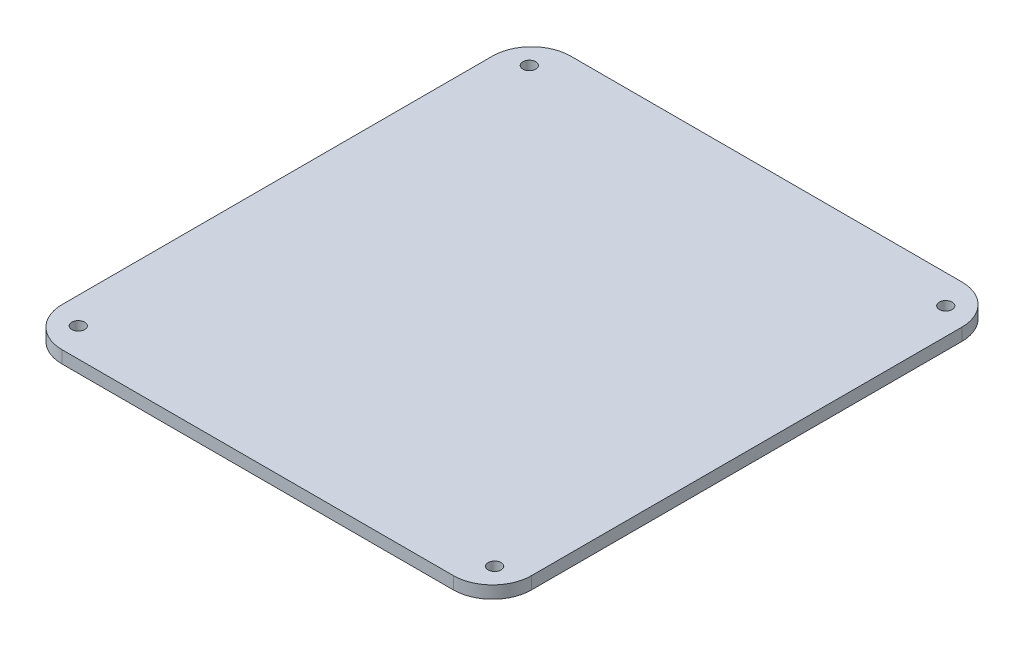
SolidWorks part; units mm, degrees
ref_plane "Front Plane" through (0, 0, 0) normal (0, 0, 1) x (1, 0, 0)
ref_plane "Top Plane" through (0, 0, 0) normal (0, 1, 0) x (1, 0, 0)
ref_plane "Right Plane" through (0, 0, 0) normal (1, 0, 0) x (0, 0, -1)
sketch "Sketch1" plane through (0, 0, 0) normal (0, 1, 0) x (1, 0, 0)
  line L0 (-60, 0) -> (60, 0) construction
  line L1 (-60, 65) -> (60, 65)
  line L2 (-60, 65) -> (-60, -65)
  line L3 (-60, -65) -> (60, -65)
  line L4 (60, 65) -> (60, -65)
  line L11 (0, 65) -> (0, -65) construction
  line L54 (-60, -65) -> (60, 65) construction
  line L55 (-60, 65) -> (60, -65) construction
  circle A10 centre (53.2172, -57.652) radius 1.65
  circle A11 centre (53.2172, 57.652) radius 1.65
  circle A12 centre (-53.2172, -57.652) radius 1.65
  circle A13 centre (-53.2172, 57.652) radius 1.65
  dimension "D27" = 3.3
  dimension "D13" = 120
  dimension "D14" = 130
  dimension "D26" = 10
extrude "Boss-Extrude1" add sketch "Sketch1" along normal blind 3.175
fillet "Fillet1" radius 10 4 edges at (60, 1.5875, -65) (60, 1.5875, 65) (-60, 1.5875, 65) (-60, 1.5875, -65)
